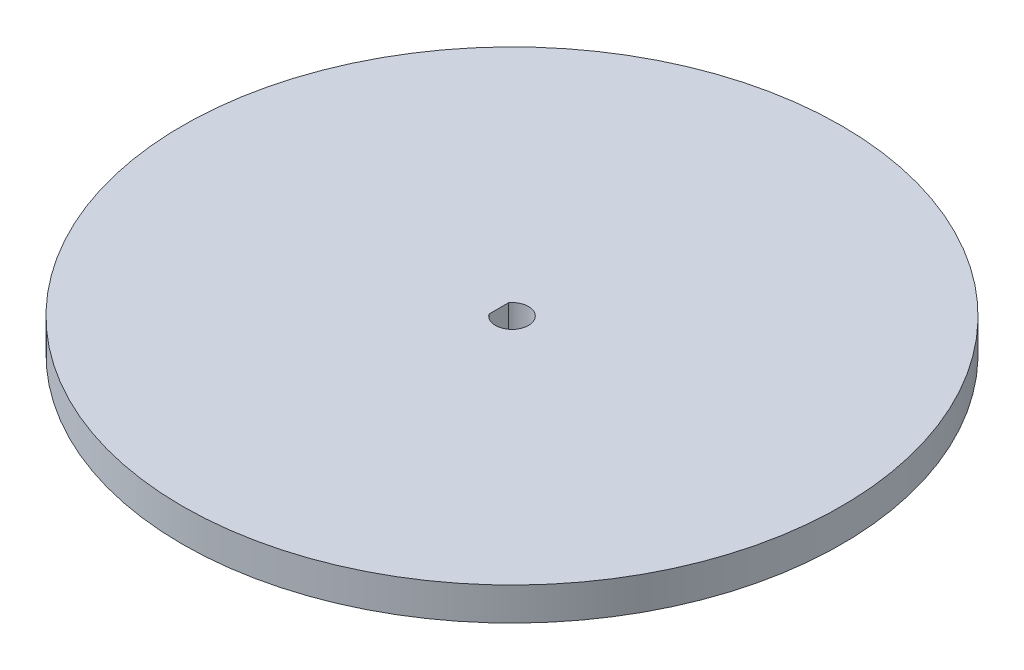
SolidWorks part; units mm, degrees
material "1.4000 (X6Cr13)"
ref_plane "前视基准面" through (0, 0, 0) normal (0, 0, 1) x (1, 0, 0)
ref_plane "上视基准面" through (0, 0, 0) normal (0, 1, 0) x (1, 0, 0)
ref_plane "右视基准面" through (0, 0, 0) normal (1, 0, 0) x (0, 0, -1)
other "Configuration Table"
sketch "草图1" plane through (0, 0, 0) normal (0, 1, 0) x (1, 0, 0)
  line L0 (-4, 3) -> (-4, -3)
  arc A0 (-4, -3) -> (-4, 3) centre (0, 0) ccw
  circle A1 centre (0, 0) radius 100
  dimension "D1" = 10
  dimension "D3" = 200
  dimension "D2" = 6
extrude "凸台-拉伸1" add sketch "草图1" along normal blind 10
sketch "草图2" plane through (0, 10, 0) normal (0, 1, 0) x (1, 0, 0)
  line L0 (-13.0825, 0) -> (-57.0566, 0) construction
sketch "草图3" plane through (0, 10, 0) normal (0, 1, 0) x (1, 0, 0)
  line L0 (0, 57.1198) -> (0, -57.4157)
  line L1 (0, 0) -> (35.2112, 0)
ref_plane "基准面1" through (0, 10, 0) normal (1, 0, 0) x (0, 0, -1)
